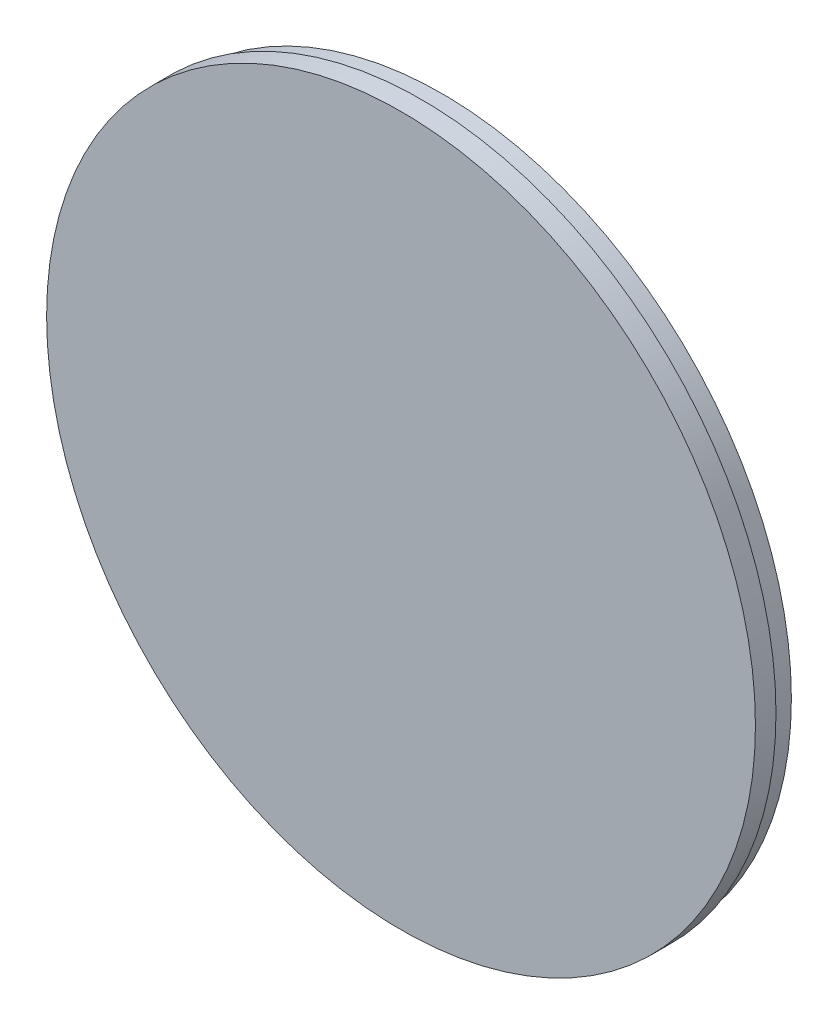
SolidWorks part; units mm, degrees
ref_plane "Front Plane" through (0, 0, 0) normal (0, 0, 1) x (1, 0, 0)
ref_plane "Top Plane" through (0, 0, 0) normal (0, 1, 0) x (1, 0, 0)
ref_plane "Right Plane" through (0, 0, 0) normal (1, 0, 0) x (0, 0, -1)
sketch "Sketch1" plane through (0, 0, 0) normal (0, 0, 1) x (1, 0, 0)
  circle A0 centre (0, 0) radius 17
  dimension "D1" = 34
extrude "Boss-Extrude1" add sketch "Sketch1" along normal blind 1
sketch "Sketch2" plane through (0, 0, 1) normal (0, 0, 1) x (1, 0, 0)
  circle A0 centre (0, 0) radius 17.25
  dimension "D1" = 34.5
extrude "Boss-Extrude2" add sketch "Sketch2" along normal blind 1
